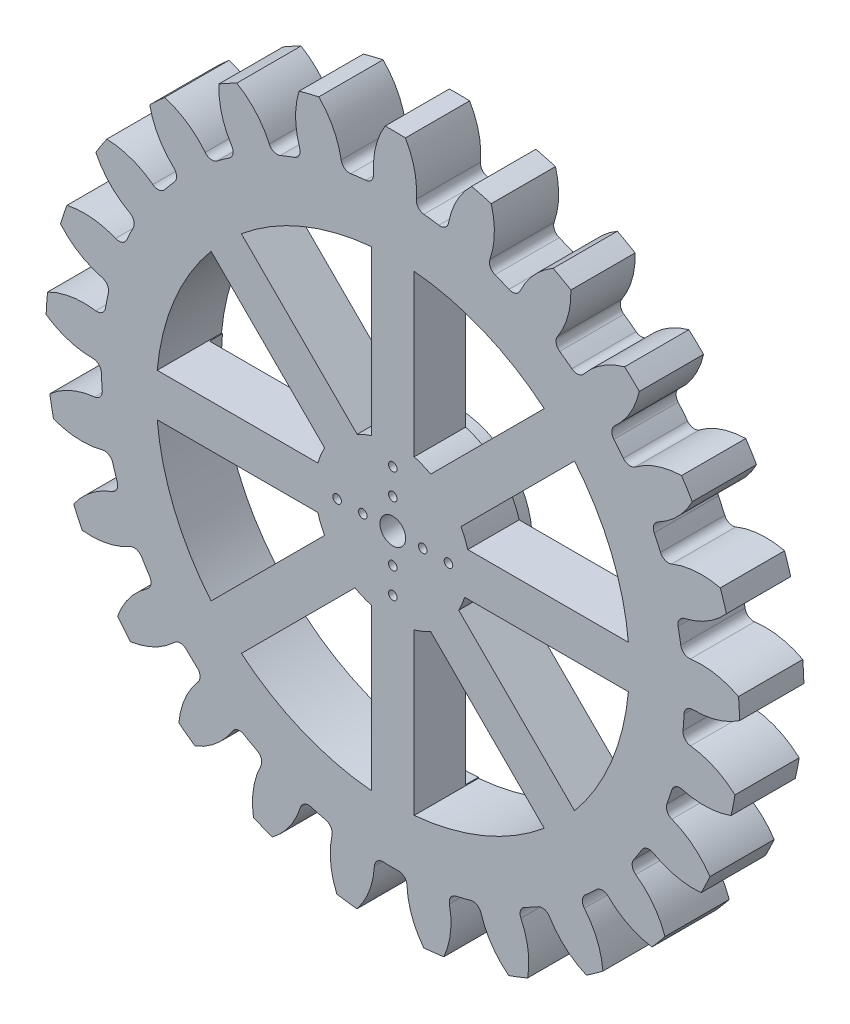
SolidWorks part; units mm, degrees
ref_plane "Front Plane" through (0, 0, 0) normal (0, 0, 1) x (1, 0, 0)
ref_plane "Top Plane" through (0, 0, 0) normal (0, 1, 0) x (1, 0, 0)
ref_plane "Right Plane" through (0, 0, 0) normal (1, 0, 0) x (0, 0, -1)
sketch "Basic Circles" plane through (0, 0, 0) normal (0, 0, 1) x (1, 0, 0)
  line L0 (0, 0) -> (0, 50000) construction
  line L2 (0, 0) -> (-50000, 0) construction
  circle A0 centre (0, 0) radius 68.058
  circle A1 centre (0, 0) radius 75
  circle A2 centre (0, 0) radius 81
sketch "Q-Circles" plane through (0, 0, 0) normal (0, 0, 1) x (1, 0, 0)
  line L0 (0, 0) -> (48.2091, 57.4533)
  line L1 (200000, 0) -> (-250000, 0) construction
  line L2 (0, -200000) -> (0, 250000) construction
  circle A0 centre (0, 0) radius 75 construction
  arc A1 (48.2091, 57.4533) -> (0, 0) centre (24.1045, 28.7267) cw construction
  arc A2 (36.1568, 43.09) -> (64.7633, 48.6489) centre (48.2091, 57.4533) ccw construction
  circle A3 centre (0, 0) radius 81 construction
  circle A4 centre (0, 0) radius 72.6184 construction
  point P3 (36.1568, 43.09)
  point P4 (48.2091, 57.4533)
  point P13 (59.1032, 42.1929)
  dimension "D3" = 18.75
  dimension "D2" = 37.5
sketch "Pressure Angle Circle" plane through (0, 0, 0) normal (0, 0, 1) x (1, 0, 0)
  line L0 (0, 0) -> (-13.0236, 73.8606)
  line L1 (0, -200000) -> (0, 250000) construction
  line L2 (34.5306, 68.9309) -> (61.8875, 45.9757) construction
  line L3 (15.042, 76.6023) -> (81.3761, 38.3043) construction
  line L4 (0, 0) -> (37.5, 64.9519)
  line L5 (0, 0) -> (48.2091, 57.4533) construction
  circle A0 centre (0, 0) radius 73.8606 construction
  circle A1 centre (0, 0) radius 75 construction
  point P10 (48.2091, 57.4533)
  point P11 (48.2091, 57.4533)
  point P16 (48.2091, 57.4533)
  point P18 (36.9303, 63.9651)
  dimension "D3" = 10
sketch "Pitch points" plane through (0, 0, 0) normal (0, 0, 1) x (1, 0, 0)
  line L0 (0, 0) -> (40.6321, 63.0399) construction
  line L1 (0, 0) -> (32.4107, 67.6354) construction
  circle A2 centre (0, 0) radius 75 construction
  circle A3 centre (0, 0) radius 75 construction
  point P1 (12.5058, 70.9056)
  point P4 (18.638, 69.5458)
  point P5 (24.6284, 67.6568)
  point P6 (30.4314, 65.2528)
  point P9 (36.0028, 62.3522)
  point P10 (40.6321, 63.0399)
  point P15 (32.4107, 67.6354)
  point P16 (23.6782, 71.1642)
  point P21 (14.5723, 73.5707)
  point P22 (5.2365, 74.817)
  point P23 (-4.1818, 74.8833)
  point P28 (-13.5342, 73.7687)
  point P29 (-22.6732, 71.4907)
  point P30 (-31.4546, 68.0853)
  point P31 (-39.7399, 63.6061)
  dimension "D2" = 7.2
  dimension "D1" = 9.42
  dimension "D3" = 10
sketch "Q-Circles (Even No Points)" plane through (0, 0, 0) normal (0, 0, 1) x (1, 0, 0)
  line L0 (0, 0) -> (-30.5449, 65.8821) construction
  line L1 (0, 0) -> (-13.2011, 71.4085) construction
  circle A0 centre (0, 0) radius 72.6184 construction
  circle A1 centre (0, 0) radius 72.6184 construction
  circle A3 centre (0, 0) radius 68.058 construction
  circle A4 centre (0, 0) radius 81 construction
  arc A5 (-49.7384, 63.9304) -> (-42.6448, 53.0407) centre (-31.4546, 68.0853) ccw
  arc A6 (-28.1144, 61.9796) -> (-32.277, 74.2913) centre (-13.5342, 73.7687) cw
  point P10 (-45.9695, 56.216)
  point P13 (-30.5449, 65.8821)
  point P15 (-13.2011, 71.4085)
  point P20 (4.9722, 72.448)
  point P23 (22.8331, 68.9354)
  point P24 (39.2593, 61.0913)
  dimension "D1" = 18.75
  dimension "D2" = 18.75
  dimension "D3" = 14.4
  dimension "D4" = 5
sketch "Q-Circles (Odd No Points)" plane through (0, 0, 0) normal (0, 0, 1) x (1, 0, 0)
  line L0 (0, 0) -> (-3.951, 72.5109) construction
  line L1 (0, 0) -> (14.2059, 71.2154) construction
  circle A0 centre (0, 0) radius 72.6184 construction
  circle A3 centre (0, 0) radius 72.6184 construction
  arc A5 (-21.0236, 64.7294) -> (-26.25, 76.6286) centre (-39.7399, 63.6061) ccw
  arc A6 (-4.2655, 67.9242) -> (-6.3685, 80.7493) centre (-22.6732, 71.4907) ccw
  circle A7 centre (0, 0) radius 68.058 construction
  circle A8 centre (0, 0) radius 81 construction
  point P14 (-3.951, 72.5109)
  point P17 (14.2059, 71.2154)
  point P21 (31.4701, 65.4452)
  point P22 (46.757, 55.5628)
  point P23 (-21.8596, 69.2503)
  point P24 (59.1059, 42.1892)
  dimension "D1" = 18.75
  dimension "D2" = 18.75
  dimension "D3" = 14.4
  dimension "D4" = 5
sketch "Gear Profile" plane through (0, 0, 0) normal (0, 0, 1) x (1, 0, 0)
  arc A1 (-28.1256, 61.9745) -> (-36.4185, 72.3512) centre (-45.9695, 56.216) ccw
  arc A5 (-36.4502, 57.4741) -> (-40.5905, 70.0957) centre (-21.8596, 69.2503) cw
  arc A6 (-11.8296, 67.022) -> (-17.2814, 79.135) centre (-30.5449, 65.8821) ccw
  arc A7 (-21.0118, 64.7333) -> (-21.8832, 77.988) centre (-3.951, 72.5109) cw
  circle A8 centre (0, 0) radius 68.058 construction
  circle A9 centre (0, 0) radius 81 construction
sketch "Sketch12" plane through (0, 0, 0) normal (0, 0, 1) x (1, 0, 0)
  circle A0 centre (0, 0) radius 68.058 construction
  circle A1 centre (0, 0) radius 68.058
extrude "Boss-Extrude2" add sketch "Sketch12" along normal mid plane 15
sketch "Sketch13" plane through (0, 0, 0) normal (0, 0, 1) x (1, 0, 0)
  circle A4 centre (0, 0) radius 68.058 construction
  circle A5 centre (0, 0) radius 81 construction
  arc A6 (-28.1256, 61.9745) -> (-36.4185, 72.3512) centre (-45.9695, 56.216) ccw construction
  arc A7 (-40.5905, 70.0957) -> (-36.4502, 57.4741) centre (-21.8596, 69.2503) ccw construction
  arc A8 (-28.1256, 61.9745) -> (-36.4502, 57.4741) centre (0, 0) ccw
  arc A9 (-36.4185, 72.3512) -> (-40.5905, 70.0957) centre (0, 0) ccw
  arc A10 (-28.1256, 61.9745) -> (-36.4185, 72.3512) centre (-45.9695, 56.216) ccw
  arc A11 (-40.5905, 70.0957) -> (-36.4502, 57.4741) centre (-21.8596, 69.2503) ccw
extrude "Boss-Extrude3" add sketch "Sketch13" along normal mid plane 15
fillet "Fillet1" radius 2 2 edges at (-36.4502, 57.4741, 0) (-28.1256, 61.9745, 0)
pattern_circular "CirPattern2" count 25 over 360 about axis through (0, 0, 0) along (0, 0, 1) of "Boss-Extrude3", "Fillet1"
sketch "Croquis1" plane through (0, 0, -7.5) normal (0, 0, -1) x (-1, 0, 0)
  line L0 (0, 0) -> (7, 0) construction
  line L1 (0, 0) -> (-7, 0) construction
  line L2 (7, 0) -> (13, 0) construction
  line L3 (-7, 0) -> (-13, 0) construction
  circle A0 centre (0, 0) radius 18 construction
  circle A1 centre (7, 0) radius 1
  circle A2 centre (13, 0) radius 1
  circle A3 centre (-7, 0) radius 1
  circle A4 centre (-13, 0) radius 1
  dimension "D1" = 36
  dimension "D3" = 2
  dimension "D5" = 2
  dimension "D8" = 2
  dimension "D9" = 2
  dimension "D2" = 7
  dimension "D4" = 6
  dimension "D6" = 7
  dimension "D7" = 6
extrude "Cortar-Extruir1" cut sketch "Croquis1" against normal blind 15
sketch "Croquis2" plane through (0, 0, -7.5) normal (0, 0, -1) x (-1, 0, 0)
  circle A0 centre (0, 0) radius 2
  dimension "D1" = 4
extrude "Cortar-Extruir2" cut sketch "Croquis2" against normal blind 15
sketch "Sketch14" plane through (0, 0, -7.5) normal (0, 0, -1) x (-1, 0, 0)
  line L0 (0, 0) -> (0, 7) construction
  line L1 (0, 7) -> (0, 13) construction
  line L2 (0, 0) -> (0, -7) construction
  line L3 (0, -7) -> (0, -13) construction
  circle A0 centre (0, 7) radius 1
  circle A1 centre (0, 13) radius 1
  circle A2 centre (0, -7) radius 1
  circle A3 centre (0, -13) radius 1
  dimension "D2" = 2
  dimension "D4" = 2
  dimension "D7" = 2
  dimension "D8" = 2
  dimension "D1" = 7
  dimension "D3" = 6
  dimension "D5" = 7
  dimension "D6" = 6
extrude "Cut-Extrude1" cut sketch "Sketch14" against normal blind 15
sketch "Sketch15" plane through (0, 0, -7.5) normal (0, 0, -1) x (-1, 0, 0)
  line L0 (0, 17.5) -> (0, 55) construction
  line L1 (-17.5, 0) -> (-55, 0) construction
  line L2 (0, -17.5) -> (0, -55)
  line L3 (17.5, 0) -> (55, 0) construction
  line L4 (-12.3744, 12.3744) -> (-38.8909, 38.8909) construction
  line L5 (-12.3744, -12.3744) -> (-38.8909, -38.8909) construction
  line L6 (12.3744, -12.3744) -> (38.8909, -38.8909) construction
  line L7 (12.3744, 12.3744) -> (38.8909, 38.8909) construction
  line L8 (-8.8388, 15.9099) -> (-35.3553, 42.4264)
  line L9 (5, 17.5) -> (5, 55) construction
  line L10 (15.9099, 8.8388) -> (42.4264, 35.3553)
  line L11 (17.5, -5) -> (55, -5)
  line L12 (8.8388, -15.9099) -> (35.3553, -42.4264)
  line L13 (-5, -17.5) -> (-5, -55)
  line L14 (-15.9099, -8.8388) -> (-42.4264, -35.3553) construction
  line L15 (-17.5, 5) -> (-55, 5)
  line L16 (-15.9099, 8.8388) -> (-42.4264, 35.3553)
  line L17 (-5, 17.5) -> (-5, 55)
  line L19 (17.5, 5) -> (55, 5)
  line L20 (15.9099, -8.8388) -> (42.4264, -35.3553)
  line L21 (5, -17.5) -> (5, -55)
  line L22 (-8.8388, -15.9099) -> (-35.3553, -42.4264)
  line L23 (-17.5, -5) -> (-55, -5) construction
  line L24 (-15.9099, -8.8388) -> (-42.4264, -35.3553) construction
  line L25 (-15.9099, 8.8388) -> (-42.4264, 35.3553) construction
  line L27 (8.8388, 15.9099) -> (35.3553, 42.4264) construction
  line L28 (5, 17.5) -> (5, 55) construction
  circle A27 centre (0, 0) radius 55 construction
  circle A28 centre (0, 0) radius 17.5 construction
  arc A29 (5, 17.5) -> (8.8388, 15.9099) centre (0, 0) cw construction
  arc A30 (17.5, 5) -> (15.9099, 8.8388) centre (0, 0) ccw
  arc A31 (15.9099, -8.8388) -> (17.5, -5) centre (0, 0) ccw
  arc A32 (5, -17.5) -> (8.8388, -15.9099) centre (0, 0) ccw
  arc A33 (-8.8388, -15.9099) -> (-5, -17.5) centre (0, 0) ccw
  arc A34 (-17.5, -5) -> (-15.9099, -8.8388) centre (0, 0) ccw construction
  arc A35 (-17.5, 5) -> (-15.9099, 8.8388) centre (0, 0) cw
  arc A36 (-5, 17.5) -> (-8.8388, 15.9099) centre (0, 0) ccw
  arc A37 (42.4264, 35.3553) -> (55, 5) centre (0, 0) cw
  arc A38 (42.4264, -35.3553) -> (55, -5) centre (0, 0) ccw
  arc A39 (5, -55) -> (35.3553, -42.4264) centre (0, 0) ccw
  arc A40 (-35.3553, -42.4264) -> (-5, -55) centre (0, 0) ccw
  arc A41 (-5, 55) -> (-35.3553, 42.4264) centre (0, 0) ccw
  arc A42 (-42.4264, 35.3553) -> (-55, 5) centre (0, 0) ccw
  dimension "D1" = 110
  dimension "D2" = 45
  dimension "D4" = 35
  dimension "D3" = 45
  dimension "D5" = 5
  dimension "D6" = 5
  dimension "D7" = 5
extrude "Cut-Extrude3" cut sketch "Sketch15" against normal blind 15 contours A37 L10 A30 L19 | L17 A41 L8 A36 | L16 A42 L15 A35 | L22 A40 L13 A33 | L21 A39 L12 A32 | L20 A38 L11 A31
sketch "Sketch17" plane through (0, 0, -7.5) normal (0, 0, -1) x (-1, 0, 0)
sketch "Sketch18" plane through (0, 0, -7.5) normal (0, 0, -1) x (-1, 0, 0)
  line L0 (0, 0) -> (0, 55) construction
  line L1 (5, 16.7705) -> (5, 55)
  line L2 (0, 0) -> (38.8909, 38.8909) construction
  line L3 (8.323, 15.3941) -> (35.3553, 42.4264)
  line L4 (-3.5355, 3.5355) -> (35.3553, 42.4264) construction
  line L5 (5, 0) -> (5, 55) construction
  line L6 (0, 0) -> (-55, 0) construction
  line L7 (-16.7705, -5) -> (-55, -5)
  line L8 (0, 0) -> (-38.8909, -38.8909) construction
  line L10 (-15.3941, -8.323) -> (-42.4264, -35.3553)
  line L11 (0, -5) -> (-55, -5) construction
  line L12 (-12.0711, -5) -> (-42.4264, -35.3553) construction
  line L13 (-12.0711, -5) -> (-55, -5) construction
  circle A0 centre (0, 0) radius 17.5 construction
  arc A1 (35.3553, 42.4264) -> (5, 55) centre (0, 0) ccw
  arc A2 (-55, -5) -> (-42.4264, -35.3553) centre (0, 0) ccw
  arc A3 (-16.7705, -5) -> (-15.3941, -8.323) centre (0, 0) ccw
  arc A4 (8.323, 15.3941) -> (5, 16.7705) centre (0, 0) ccw
  dimension "D1" = 35
  dimension "D2" = 5
  dimension "D3" = 5
  dimension "D4" = 45
  dimension "D7" = 45
  dimension "D6" = 5
  dimension "D8" = 5
extrude "Cut-Extrude4" cut sketch "Sketch18" against normal blind 15
sketch "Sketch19" plane through (0, 0, -7.5) normal (0, 0, -1) x (-1, 0, 0)
  circle A0 centre (0, 0) radius 17.5
  circle A1 centre (0, 0) radius 55
  dimension "D1" = 35
  dimension "D2" = 110
extrude "Cut-Extrude5" cut sketch "Sketch19" against normal blind 3
sketch "Sketch20" plane through (0, 0, 7.5) normal (0, 0, 1) x (1, 0, 0)
  circle A0 centre (0, 0) radius 3
  dimension "D1" = 6
extrude "Cut-Extrude6" cut sketch "Sketch20" against normal blind 15
equation "\"module\"= 6"
equation "\"no of teeth\"= 25"
equation "\"addendum\"= \"module\" * 1"
equation "\"clearence\"= \"module\" * .157"
equation "\"dedendum\"= \"addendum\" + \"clearence\""
equation "\"circular pitch\"= \"module\" * 3.14"
equation "\"D1@Basic Circles\" = \"module\" * \"no of teeth\""
equation "\"D2@Basic Circles\"= \"D1@Basic Circles\" + 2 * \"addendum\""
equation "\"D3@Basic Circles\" = \"D1@Basic Circles\" - 2 * \"dedendum\""
equation "\"D3@Q-Circles\"= \"module\" * \"no of teeth\" / 8"
equation "\"D1@Boss-Extrude2\"=\"module\"*2.5"
equation "\"D1@Boss-Extrude3\"=\"module\"*2.5"
equation "\"D1@Pitch points\"   = \"circular pitch\" / 2"
equation "\"D2@Pitch points\"   = ( \"D1@Pitch points\" * 360 ) / ( 3.14 * \"module\" * \"no of teeth\" )"
equation "\"D1@Q-Circles (Even No Points)\"= \"module\" * \"no of teeth\" / 8"
equation "\"D2@Q-Circles (Even No Points)\" = \"module\" * \"no of teeth\" / 8"
equation "\"D3@Q-Circles (Even No Points)\" = ( \"circular pitch\" / 2 * 360 ) / ( \"module\" * \"no of teeth\" * 3.14 ) * 2"
equation "\"D1@Q-Circles (Odd No Points)\"   = \"module\" * \"no of teeth\" / 8"
equation "\"D2@Q-Circles (Odd No Points)\"   = \"module\" * \"no of teeth\" / 8"
equation "\"D3@Q-Circles (Odd No Points)\" = ( \"circular pitch\" / 2 * 360 ) / ( \"module\" * \"no of teeth\" * 3.14 ) * 2"
equation "\"D1@CirPattern2\" = \"no of teeth\""
equation "\"Pressure Angle\"= 10deg"
equation "\"D2@Pressure Angle Circle\" = \"Pressure Angle\""
equation "\"D3@Pressure Angle Circle\" = \"Pressure Angle\""
equation "\"D1@Pressure Angle Circle\" = \"Pressure Angle\""
